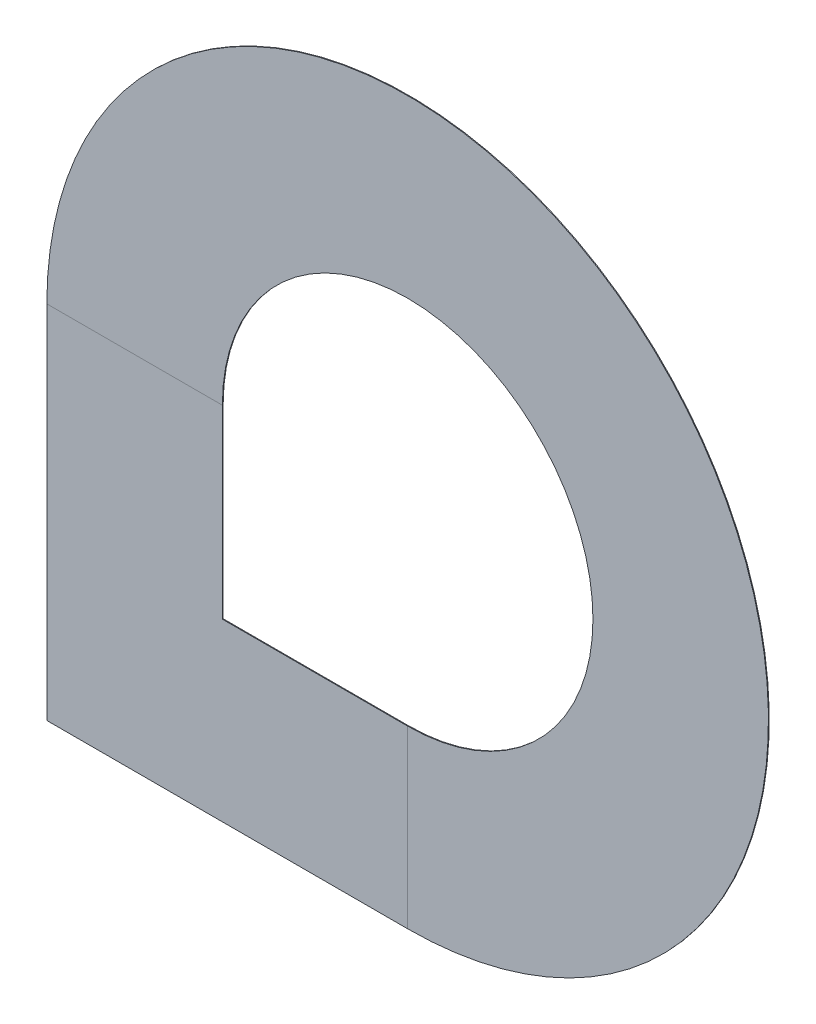
SolidWorks part; units mm, degrees
ref_plane "前视基准面" through (0, 0, 0) normal (0, 0, 1) x (1, 0, 0)
ref_plane "上视基准面" through (0, 0, 0) normal (0, 1, 0) x (1, 0, 0)
ref_plane "右视基准面" through (0, 0, 0) normal (1, 0, 0) x (0, 0, -1)
sketch "草图1" plane through (0, 0, 0) normal (0, 0, 1) x (1, 0, 0)
  line L1 (0, 0) -> (0, 700)
  line L3 (700, 0) -> (0, 0)
  arc A1 (0, 700) -> (700, 0) centre (700, 700) cw
  dimension "D1" = 700
sketch "草图2" plane through (0, 0, 0) normal (0, 1, 0) x (1, 0, 0)
  line L1 (-225, 1) -> (225, 1)
  line L2 (-225, 1) -> (-225, -1)
  line L3 (-225, -1) -> (225, -1)
  line L4 (225, 1) -> (225, -1)
  line L5 (-225, 1) -> (225, -1) construction
  line L6 (-225, -1) -> (225, 1) construction
  point P0 (0, 0)
  dimension "D1" = 450
  dimension "D2" = 2
sweep "扫描1" add profiles "草图2" path "草图1"
